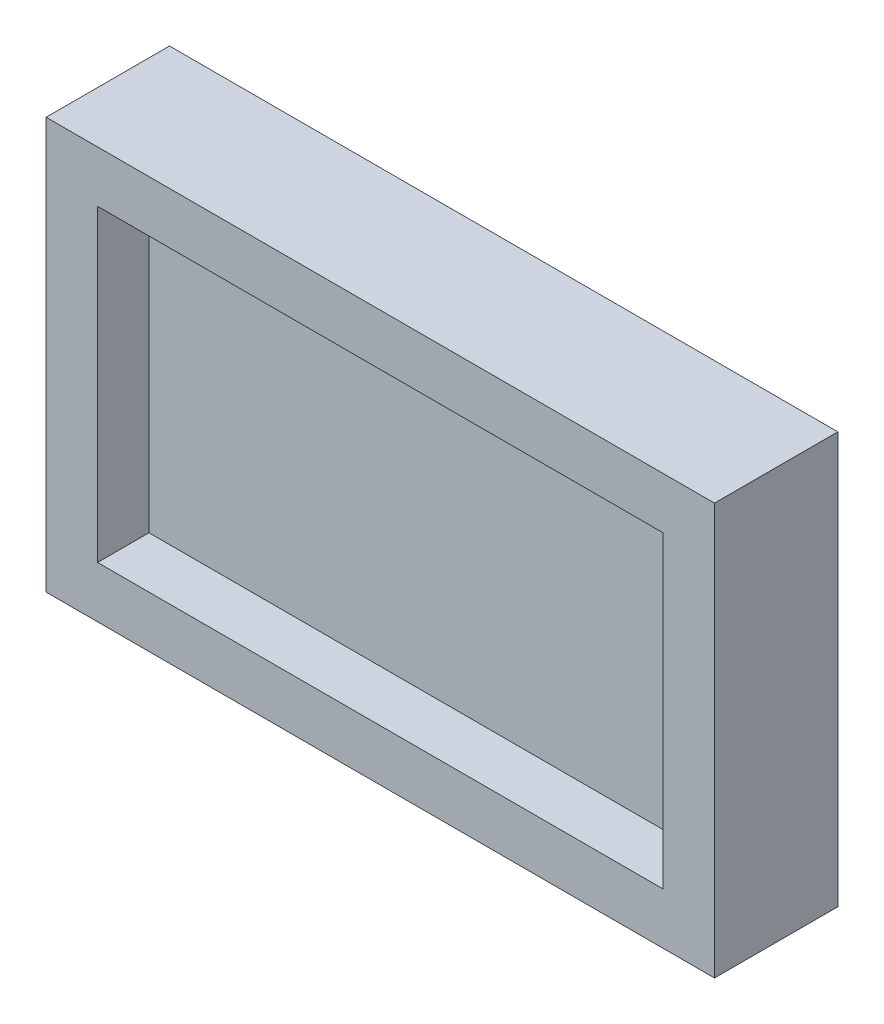
SolidWorks part; units mm, degrees
ref_plane "前视基准面" through (0, 0, 0) normal (0, 0, 1) x (1, 0, 0)
ref_plane "上视基准面" through (0, 0, 0) normal (0, 1, 0) x (1, 0, 0)
ref_plane "右视基准面" through (0, 0, 0) normal (1, 0, 0) x (0, 0, -1)
sketch "草图1" plane through (0, 0, 0) normal (0, 0, 1) x (1, 0, 0)
  line L1 (-17.1111, 14.6222) -> (47.8889, 14.6222)
  line L2 (-17.1111, 14.6222) -> (-17.1111, -25.3778)
  line L3 (-17.1111, -25.3778) -> (47.8889, -25.3778)
  line L4 (47.8889, 14.6222) -> (47.8889, -25.3778)
  dimension "D1" = 40
  dimension "D2" = 65
extrude "凸台-拉伸2" add sketch "草图1" along normal blind 12
sketch "草图3" plane through (0, 0, 12) normal (0, 0, 1) x (1, 0, 0)
  line L0 (-17.1111, 14.6222) -> (-17.1111, -25.3778) construction
  line L1 (-12.1111, 9.6222) -> (42.8889, 9.6222)
  line L2 (-12.1111, 9.6222) -> (-12.1111, -20.3778)
  line L3 (-12.1111, -20.3778) -> (42.8889, -20.3778)
  line L4 (42.8889, 9.6222) -> (42.8889, -20.3778)
  line L5 (47.8889, 14.6222) -> (-17.1111, 14.6222) construction
  dimension "D1" = 5
  dimension "D2" = 55
  dimension "D3" = 5
  dimension "D4" = 30
extrude "切除-拉伸1" cut sketch "草图3" against normal blind 5
